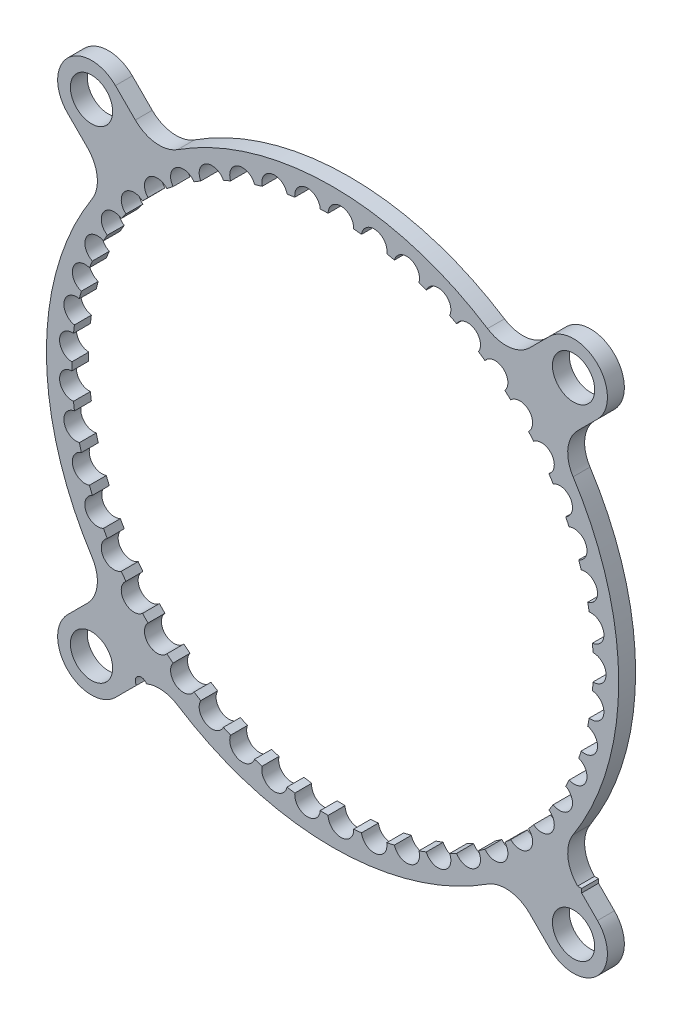
SolidWorks part; units mm, degrees
ref_plane "前视基准面" through (0, 0, 0) normal (0, 0, 1) x (1, 0, 0)
ref_plane "上视基准面" through (0, 0, 0) normal (0, 1, 0) x (1, 0, 0)
ref_plane "右视基准面" through (0, 0, 0) normal (1, 0, 0) x (0, 0, -1)
sketch "草图1" plane through (0, 0, 0) normal (0, 0, 1) x (1, 0, 0)
  line L103 (0, 0) -> (0, -23.55) construction
  line L104 (28.4997, -28.4997) -> (33.4495, -23.55) construction
  line L119 (23.55, -23.55) -> (28.4997, -28.4997) construction
  line L120 (33.4495, -23.55) -> (24.8719, -32.1276) construction
  line L124 (25.6713, -31.3282) -> (23.3201, -28.9769)
  line L126 (-31.3282, -25.6713) -> (-28.9769, -23.3201)
  line L127 (-25.6713, -31.3282) -> (-23.3201, -28.9769)
  line L128 (-25.6713, 31.3282) -> (-23.3201, 28.9769)
  line L129 (-31.3282, 25.6713) -> (-28.9769, 23.3201)
  line L130 (31.3282, 25.6713) -> (28.9769, 23.3201)
  line L131 (25.6713, 31.3282) -> (23.3201, 28.9769)
  line L132 (28.9769, -23.3201) -> (29.4503, -23.3201)
  line L133 (29.4503, -23.3201) -> (29.4503, -23.7934)
  line L134 (29.4503, -23.7934) -> (31.3282, -25.6713)
  circle A3 centre (30.83, 0) radius 1.51
  circle A4 centre (30.5769, -3.9425) radius 1.51
  circle A5 centre (29.8217, -7.8202) radius 1.51
  circle A6 centre (28.5768, -11.5695) radius 1.51
  circle A7 centre (26.8628, -15.1288) radius 1.51
  circle A8 centre (24.7076, -18.4397) radius 1.51
  circle A9 centre (22.1467, -21.4479) radius 1.51
  circle A10 centre (19.2222, -24.1039) radius 1.51
  circle A11 centre (15.982, -26.3641) radius 1.51
  circle A12 centre (12.4795, -28.1913) radius 1.51
  circle A13 centre (8.772, -29.5557) radius 1.51
  circle A14 centre (4.9205, -30.4348) radius 1.51
  circle A15 centre (0.9882, -30.8142) radius 1.51
  circle A16 centre (-2.9604, -30.6875) radius 1.51
  circle A17 centre (-6.8603, -30.057) radius 1.51
  circle A18 centre (-10.6476, -28.933) radius 1.51
  circle A19 centre (-14.2601, -27.3339) radius 1.51
  circle A20 centre (-17.6384, -25.2859) radius 1.51
  circle A21 centre (-20.727, -22.8228) radius 1.51
  circle A22 centre (-23.4754, -19.9849) radius 1.51
  circle A23 centre (-25.8383, -16.8188) radius 1.51
  circle A24 centre (-27.7769, -13.3766) radius 1.51
  circle A25 centre (-29.2594, -9.7148) radius 1.51
  circle A26 centre (-30.2615, -5.8934) radius 1.51
  circle A28 centre (-30.7667, -1.9753) radius 1.51
  circle A29 centre (-30.7667, 1.9753) radius 1.51
  circle A30 centre (-30.2615, 5.8934) radius 1.51
  circle A31 centre (-29.2594, 9.7148) radius 1.51
  circle A32 centre (-27.7769, 13.3766) radius 1.51
  circle A33 centre (-25.8383, 16.8188) radius 1.51
  circle A34 centre (-23.4754, 19.9849) radius 1.51
  circle A35 centre (-20.727, 22.8228) radius 1.51
  circle A36 centre (-17.6384, 25.2859) radius 1.51
  circle A37 centre (-14.2601, 27.3339) radius 1.51
  circle A38 centre (-10.6476, 28.933) radius 1.51
  circle A39 centre (-6.8603, 30.057) radius 1.51
  circle A40 centre (-2.9604, 30.6875) radius 1.51
  circle A41 centre (0.9882, 30.8142) radius 1.51
  circle A42 centre (4.9205, 30.4348) radius 1.51
  circle A43 centre (8.772, 29.5557) radius 1.51
  circle A44 centre (12.4795, 28.1913) radius 1.51
  circle A45 centre (15.982, 26.3641) radius 1.51
  circle A46 centre (19.2222, 24.1039) radius 1.51
  circle A47 centre (22.1467, 21.4479) radius 1.51
  circle A48 centre (24.7076, 18.4397) radius 1.51
  circle A49 centre (26.8628, 15.1288) radius 1.51
  circle A50 centre (28.5768, 11.5695) radius 1.51
  circle A168 centre (28.4997, -28.4997) radius 2.5
  circle A197 centre (28.4997, -28.4997) radius 4 construction
  arc A198 (25.6713, -31.3282) -> (31.3282, -25.6713) centre (28.4997, -28.4997) ccw
  arc A199 (-31.3282, -25.6713) -> (-25.6713, -31.3282) centre (-28.4997, -28.4997) ccw
  circle A200 centre (-28.4997, -28.4997) radius 2.5
  arc A208 (-25.6713, 31.3282) -> (-31.3282, 25.6713) centre (-28.4997, 28.4997) ccw
  circle A209 centre (-28.4997, 28.4997) radius 2.5
  arc A210 (31.3282, 25.6713) -> (25.6713, 31.3282) centre (28.4997, 28.4997) ccw
  circle A211 centre (28.4997, 28.4997) radius 2.5
  arc A212 (-18.3252, -28.4428) -> (18.3252, -28.4428) centre (0, 0) ccw
  arc A213 (28.4428, -18.3252) -> (28.4428, 18.3252) centre (0, 0) ccw
  arc A215 (-28.4428, -18.3252) -> (-28.4428, 18.3252) centre (0, 0) cw
  arc A218 (18.3252, 28.4428) -> (-18.3252, 28.4428) centre (0, 0) ccw
  arc A219 (-18.3252, 28.4428) -> (-23.3201, 28.9769) centre (-20.4916, 31.8053) cw
  arc A220 (-28.4428, 18.3252) -> (-28.9769, 23.3201) centre (-31.8053, 20.4916) ccw
  arc A221 (-18.3252, -28.4428) -> (-23.3201, -28.9769) centre (-20.4916, -31.8053) ccw
  arc A222 (-28.4428, -18.3252) -> (-28.9769, -23.3201) centre (-31.8053, -20.4916) cw
  arc A223 (18.3252, -28.4428) -> (23.3201, -28.9769) centre (20.4916, -31.8053) cw
  arc A224 (28.4428, -18.3252) -> (28.9769, -23.3201) centre (31.8053, -20.4916) ccw
  arc A225 (28.4428, 18.3252) -> (28.9769, 23.3201) centre (31.8053, 20.4916) cw
  arc A226 (23.3201, 28.9769) -> (18.3252, 28.4428) centre (20.4916, 31.8053) cw
  circle A227 centre (0, 0) radius 30.83 construction
  circle A287 centre (29.8217, 7.8202) radius 1.51
  circle A288 centre (30.5769, 3.9425) radius 1.51
  point P386 (21.4419, -26.3865)
  point P407 (26.0685, -21.8273)
  point P459 (-28.5, -28.5)
  dimension "D6" = 4
extrude "凸台-拉伸1" add sketch "草图1" along normal blind 2
sketch "草图2" plane through (0, 0, 2) normal (0, 0, 1) x (1, 0, 0)
  circle A0 centre (0, 0) radius 30.83
extrude "切除-拉伸1" cut sketch "草图2" against normal blind 2
sketch "草图3" plane through (0, 0, 2) normal (0, 0, 1) x (1, 0, 0)
  circle A0 centre (-22.625, -28.4217) radius 0.7
  arc A1 (-18.3252, -28.4428) -> (-23.3201, -28.9769) centre (-20.4916, -31.8053) ccw construction
extrude "切除-拉伸2" cut sketch "草图3" against normal blind 10
